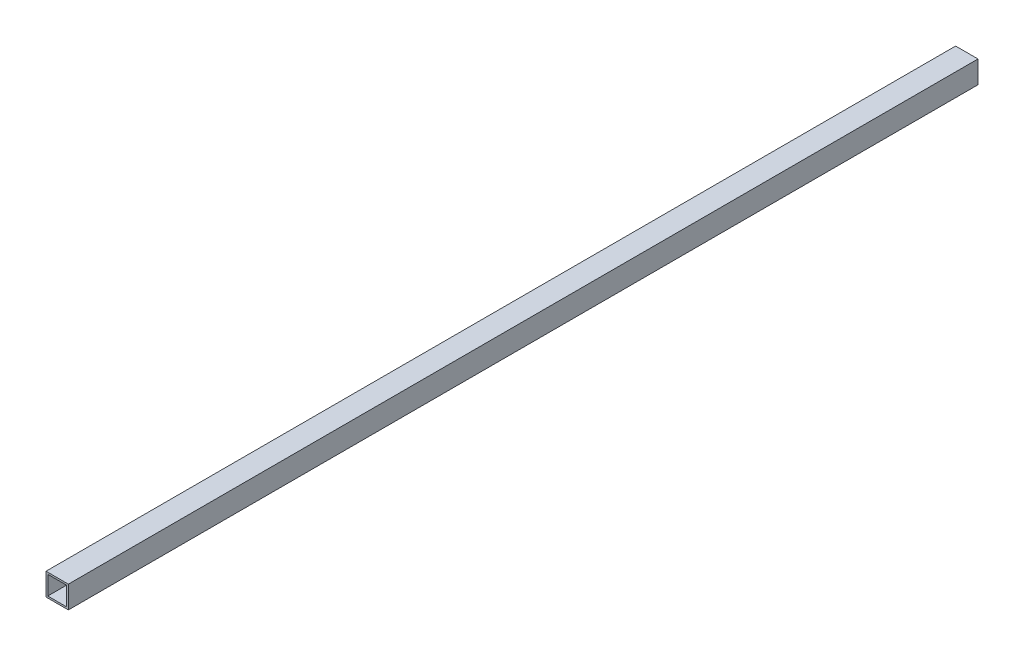
SolidWorks part; units mm, degrees
material "7050-T73510"
ref_plane "Front" through (0, 0, 0) normal (0, 0, 1) x (1, 0, 0)
ref_plane "Top" through (0, 0, 0) normal (0, 1, 0) x (1, 0, 0)
ref_plane "Right" through (0, 0, 0) normal (1, 0, 0) x (0, 0, -1)
sketch "草图1" plane through (0, 0, 0) normal (0, 0, 1) x (1, 0, 0)
  line L0 (-6.3, -6.3) -> (-6.3, 6.3)
  line L1 (-7.5, -7.5) -> (7.5, -7.5)
  line L2 (-7.5, -7.5) -> (-7.5, 7.5)
  line L3 (-7.5, 7.5) -> (7.5, 7.5)
  line L4 (7.5, -7.5) -> (7.5, 7.5)
  line L5 (-7.5, -7.5) -> (7.5, 7.5) construction
  line L6 (-7.5, 7.5) -> (7.5, -7.5) construction
  line L7 (-6.3, 6.3) -> (6.3, 6.3)
  line L8 (6.3, -6.3) -> (6.3, 6.3)
  line L9 (-6.3, -6.3) -> (6.3, -6.3)
  point P0 (0, 0)
  dimension "D1" = 15
  dimension "D2" = 15
  dimension "D3" = 1.2
extrude "凸台-拉伸1" add sketch "草图1" along normal blind 610
